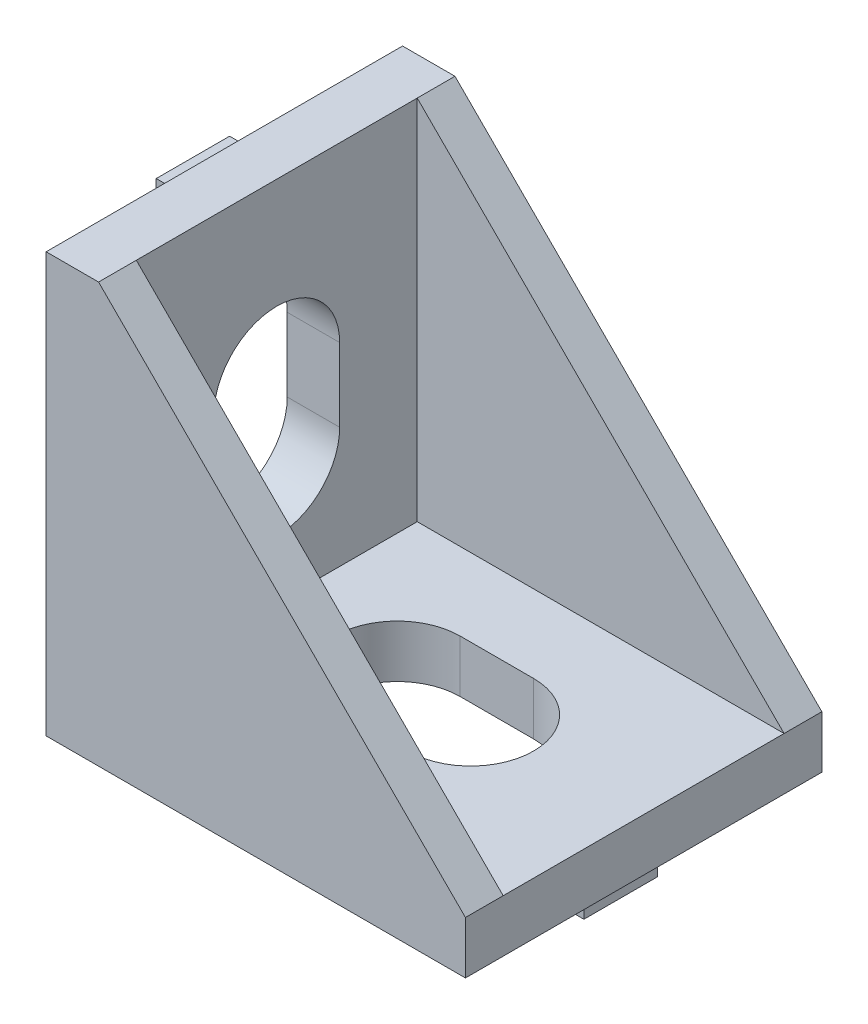
SolidWorks part; units mm, degrees
ref_plane "Front Plane" through (0, 0, 0) normal (0, 0, 1) x (1, 0, 0)
ref_plane "Top Plane" through (0, 0, 0) normal (0, 1, 0) x (1, 0, 0)
ref_plane "Right Plane" through (0, 0, 0) normal (1, 0, 0) x (0, 0, -1)
sketch "Sketch1" plane through (0, 0, 0) normal (0, 0, 1) x (1, 0, 0)
  line L0 (0, 20) -> (2.5, 20)
  line L1 (0, 0) -> (20, 0)
  line L2 (0, 0) -> (0, 20)
  line L3 (0, 20) -> (20, 20) construction
  line L4 (20, 0) -> (20, 20) construction
  line L5 (2.5, 20) -> (20, 2.5)
  line L6 (20, 2.5) -> (20, 0)
  dimension "D1" = 20
  dimension "D2" = 20
  dimension "D3" = 2.5
  dimension "D4" = 2.5
extrude "Boss-Extrude1" add sketch "Sketch1" along normal mid plane 17
sketch "Sketch2" plane through (0, 0, 0) normal (0, -1, 0) x (1, 0, 0)
  line L1 (2.5, 6.7) -> (20, 6.7)
  line L2 (2.5, 6.7) -> (2.5, -6.7)
  line L3 (2.5, -6.7) -> (20, -6.7)
  line L4 (0, -8.5) -> (20, -8.5)
  line L5 (20, -8.5) -> (20, 8.5)
  line L6 (20, 8.5) -> (0, 8.5)
  line L7 (0, 8.5) -> (0, -8.5)
  line L8 (0, -8.5) -> (20, -8.5)
  line L9 (20, -8.5) -> (20, 8.5)
  line L10 (20, 8.5) -> (0, 8.5)
  line L11 (0, 8.5) -> (0, -8.5)
  line L12 (20, 6.7) -> (20, -6.7)
  dimension "D2" = 2.5
  dimension "D3" = 1.8
  dimension "D4" = 1.8
  dimension "D1" = 0
extrude "Cut-Extrude2" cut sketch "Sketch2" against normal through all from offset 2.5 contours L2 L1 L12 L3 offset against normal yes
sketch "Sketch3" plane through (0, 2.5, 0) normal (0, 1, 0) x (1, 0, 0)
  line L0 (8.25, 0) -> (11.75, 0) construction
  line L1 (8.25, 3) -> (11.75, 3)
  line L2 (8.25, -3) -> (11.75, -3)
  line L3 (0, -8.5) -> (0, 8.5) construction
  arc A0 (8.25, 3) -> (8.25, -3) centre (8.25, 0) ccw
  arc A1 (11.75, -3) -> (11.75, 3) centre (11.75, 0) ccw
  point P3 (10, 0)
  point P8 (0, 0)
  dimension "D2" = 3
  dimension "D1" = 3.5
  dimension "D3" = 10
extrude "Cut-Extrude3" cut sketch "Sketch3" against normal blind 17
sketch "Sketch4" plane through (2.5, 0, 0) normal (1, 0, 0) x (0, 0, -1)
  line L0 (0, 8.25) -> (0, 11.75) construction
  line L1 (-3, 8.25) -> (-3, 11.75)
  line L2 (3, 8.25) -> (3, 11.75)
  line L3 (-8.5, 0) -> (8.5, 0) construction
  arc A0 (-3, 8.25) -> (3, 8.25) centre (0, 8.25) ccw
  arc A1 (3, 11.75) -> (-3, 11.75) centre (0, 11.75) ccw
  point P3 (0, 10)
  dimension "D2" = 3
  dimension "D1" = 3.5
  dimension "D3" = 10
extrude "Cut-Extrude4" cut sketch "Sketch4" against normal blind 17
sketch "Sketch5" plane through (0, 0, 0) normal (0, -1, 0) x (1, 0, 0)
  line L0 (0, 0) -> (20, 0) construction
  line L1 (20, 8.5) -> (20, -8.5) construction
  line L2 (10, 8.5) -> (10, -8.5) construction
  line L3 (1.1, 1.75) -> (2.9, 1.75)
  line L4 (1.1, 1.75) -> (1.1, -1.75)
  line L5 (1.1, -1.75) -> (2.9, -1.75)
  line L6 (2.9, 1.75) -> (2.9, -1.75)
  line L7 (1.1, 1.75) -> (2.9, -1.75) construction
  line L8 (1.1, -1.75) -> (2.9, 1.75) construction
  line L9 (0, -8.5) -> (20, -8.5) construction
  line L10 (0, 8.5) -> (20, 8.5) construction
  line L11 (18.9, -1.75) -> (17.1, 1.75) construction
  line L12 (18.9, 1.75) -> (17.1, -1.75) construction
  line L13 (17.1, 1.75) -> (17.1, -1.75)
  line L14 (18.9, -1.75) -> (17.1, -1.75)
  line L15 (18.9, 1.75) -> (18.9, -1.75)
  line L16 (18.9, 1.75) -> (17.1, 1.75)
  point P5 (2, 0)
  point P15 (10, 8.5)
  point P22 (18, 0)
  point P23 (0, 0)
  dimension "D1" = 3.5
  dimension "D2" = 1.8
  dimension "D3" = 8
extrude "Boss-Extrude2" add sketch "Sketch5" along normal blind 1.5
sketch "Sketch6" plane through (0, 0, 0) normal (-1, 0, 0) x (0, 0, 1)
  line L0 (0, 0) -> (0, 20) construction
  line L1 (8.5, 20) -> (-8.5, 20) construction
  line L2 (-8.5, 10) -> (8.5, 10) construction
  line L3 (-8.5, 20) -> (-8.5, 0) construction
  line L4 (8.5, 20) -> (8.5, 0) construction
  line L5 (-1.75, 18.9) -> (1.75, 17.1) construction
  line L6 (-1.75, 2.9) -> (1.75, 2.9)
  line L7 (-1.75, 2.9) -> (-1.75, 1.1)
  line L8 (-1.75, 1.1) -> (1.75, 1.1)
  line L9 (1.75, 2.9) -> (1.75, 1.1)
  line L10 (-1.75, 2.9) -> (1.75, 1.1) construction
  line L11 (-1.75, 1.1) -> (1.75, 2.9) construction
  line L12 (-1.75, 17.1) -> (1.75, 18.9) construction
  line L13 (1.75, 17.1) -> (1.75, 18.9)
  line L14 (-1.75, 18.9) -> (1.75, 18.9)
  line L15 (-1.75, 17.1) -> (-1.75, 18.9)
  line L16 (-1.75, 17.1) -> (1.75, 17.1)
  point P11 (0, 10)
  point P12 (0, 2)
  point P17 (0, 0)
  point P22 (0, 18)
  dimension "D1" = 1.8
  dimension "D2" = 3.5
  dimension "D3" = 8
extrude "Boss-Extrude3" add sketch "Sketch6" along normal blind 1.5
